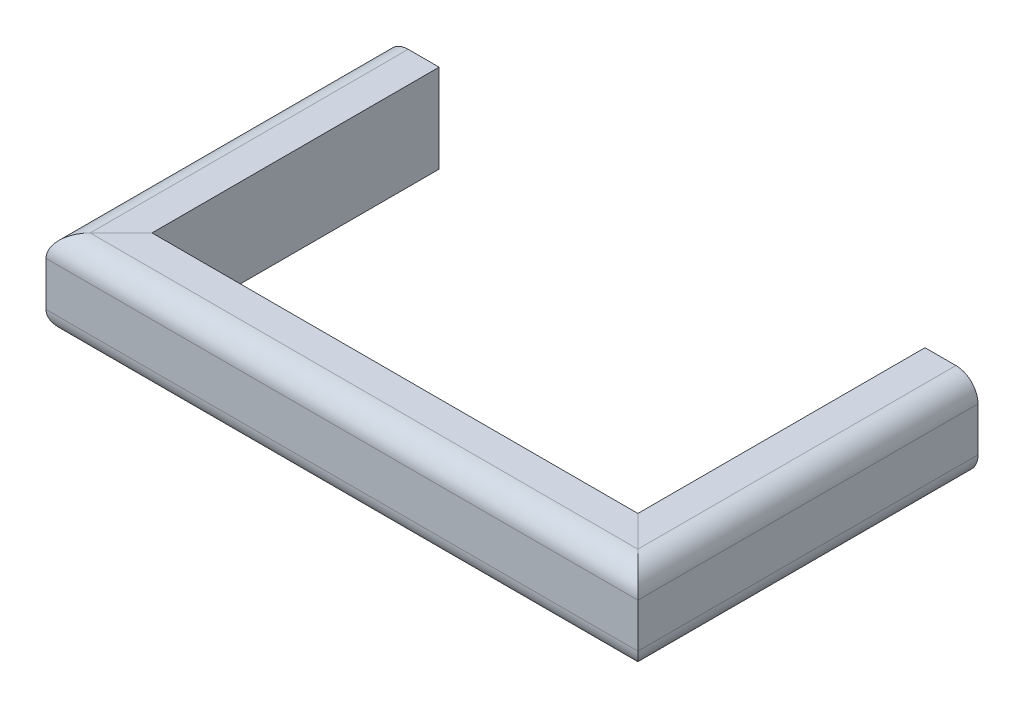
SolidWorks part; units mm, degrees
material "Polyurethane Foam Flexible"
ref_plane "Front Plane" through (0, 0, 0) normal (0, 0, 1) x (1, 0, 0)
ref_plane "Top Plane" through (0, 0, 0) normal (0, 1, 0) x (1, 0, 0)
ref_plane "Right Plane" through (0, 0, 0) normal (1, 0, 0) x (0, 0, -1)
sketch "Sketch2" plane through (0, 0, 0) normal (0, 0, 1) x (1, 0, 0)
  line L0 (0, 0) -> (-349.25, 0) construction
  line L2 (-349.25, 63.5) -> (-393.7, 63.5)
  line L3 (-349.25, 63.5) -> (-349.25, -63.5)
  line L4 (-349.25, -63.5) -> (-393.7, -63.5)
  line L5 (-425.45, 31.75) -> (-425.45, -31.75)
  arc A0 (-393.7, -63.5) -> (-425.45, -31.75) centre (-393.7, -31.75) cw
  arc A1 (-425.45, 31.75) -> (-393.7, 63.5) centre (-393.7, 31.75) cw
  point P7 (-349.25, 0)
  dimension "D2" = 31.75
  dimension "D1" = 349.25
  dimension "D3" = 127
  dimension "D4" = 44.45
sketch "Sketch3" plane through (0, 0, 0) normal (0, 1, 0) x (1, 0, 0)
  line L0 (349.25, 0) -> (-349.25, 0) construction
  line L4 (349.25, 0) -> (349.25, -412.75)
  line L5 (349.25, -412.75) -> (-349.25, -412.75)
  line L6 (-349.25, 0) -> (-349.25, -412.75)
  point P4 (0, 0)
  dimension "D1" = 412.75
sweep "Sweep1" add profiles "Sketch2" path "Sketch3"
sketch "Sketch4" plane through (0, 0, 412.75) normal (0, 0, -1) x (-1, 0, 0)
  line L0 (349.25, 63.5) -> (-349.25, 63.5) construction
  line L1 (-349.25, 63.5) -> (-349.25, -63.5) construction
  line L2 (-349.25, -63.5) -> (-349.25, 63.5) construction
  line L3 (0, -63.5) -> (0, 63.5) construction
  circle A0 centre (-342.9, 50.8) radius 3.175
  circle A1 centre (-330.2, 50.8) radius 3.175
  circle A2 centre (330.2, 50.8) radius 3.175
  circle A3 centre (342.9, 50.8) radius 3.175
  point P14 (0, 0)
  dimension "D1" = 6.35
  dimension "D2" = 12.7
  dimension "D3" = 6.35
  dimension "D4" = 19.05
extrude "Cut-Extrude1" cut sketch "Sketch4" against normal blind 12.7
